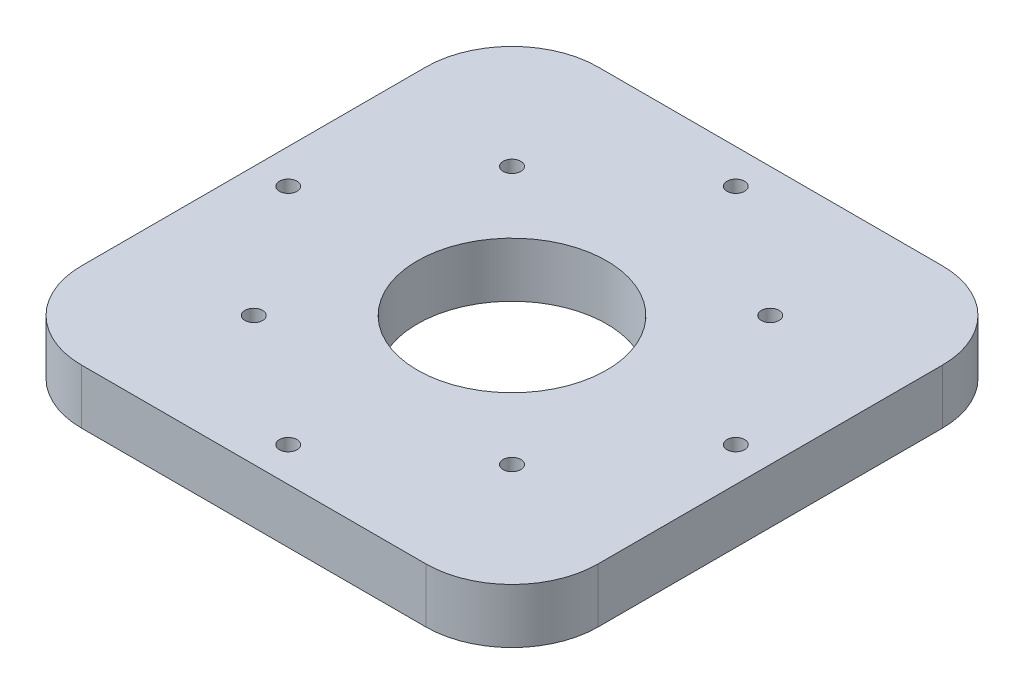
SolidWorks part; units mm, degrees
material "Oak"
ref_plane "Front Plane" through (0, 0, 0) normal (0, 0, 1) x (1, 0, 0)
ref_plane "Top Plane" through (0, 0, 0) normal (0, 1, 0) x (1, 0, 0)
ref_plane "Right Plane" through (0, 0, 0) normal (1, 0, 0) x (0, 0, -1)
sketch "Sketch3" plane through (0, 0, 0) normal (0, 1, 0) x (1, 0, 0)
  line L1 (40, -46.6704) -> (100, -46.6704)
  line L2 (40, -46.6704) -> (40, -106.6704)
  line L3 (40, -106.6704) -> (100, -106.6704)
  line L4 (100, -46.6704) -> (100, -106.6704)
  line L5 (70, -76.6704) -> (85, -76.6704) construction
  line L6 (70, -76.6704) -> (70, -91.6704) construction
  line L7 (70, -91.6704) -> (85, -91.6704) construction
  line L8 (85, -76.6704) -> (85, -91.6704) construction
  line L9 (55, -61.6704) -> (85, -61.6704) construction
  line L10 (55, -61.6704) -> (55, -91.6704) construction
  line L11 (55, -91.6704) -> (85, -91.6704) construction
  line L12 (85, -61.6704) -> (85, -91.6704) construction
  line L13 (55, -61.6704) -> (85, -91.6704) construction
  line L14 (55, -91.6704) -> (85, -61.6704) construction
  circle A0 centre (70, -76.6704) radius 11
  circle A1 centre (55, -61.6704) radius 1.025
  circle A2 centre (85, -61.6704) radius 1.025
  circle A3 centre (85, -91.6704) radius 1.025
  circle A4 centre (55, -91.6704) radius 1.025
  dimension "D5" = 22
  dimension "D8" = 2.05
  dimension "D9" = 2.05
  dimension "D10" = 2.05
  dimension "D11" = 2.05
  dimension "D1" = 60
  dimension "D2" = 60
  dimension "D3" = 30
  dimension "D4" = 30
  dimension "D6" = 15
  dimension "D7" = 15
extrude "Boss-Extrude1" add sketch "Sketch3" along normal blind 6.35
fillet "Fillet1" radius 10 4 edges at (100, 3.175, 106.6704) (100, 3.175, 46.6704) (40, 3.175, 46.6704) (40, 3.175, 106.6704)
sketch "Sketch4" plane through (0, 6.35, 0) normal (0, 1, 0) x (1, 0, 0)
  line L0 (40, -56.6704) -> (40, -96.6704) construction
  line L1 (100, -96.6704) -> (100, -56.6704) construction
  line L2 (90, -46.6704) -> (50, -46.6704) construction
  line L3 (50, -106.6704) -> (90, -106.6704) construction
  line L4 (70, -50.6704) -> (70, -102.6704) construction
  line L5 (44, -76.6704) -> (96, -76.6704) construction
  circle A0 centre (44, -76.6704) radius 1.025
  circle A1 centre (96, -76.6704) radius 1.025
  circle A2 centre (70, -50.6704) radius 1.025
  circle A3 centre (70, -102.6704) radius 1.025
  dimension "D1" = 2.05
  dimension "D2" = 2.05
  dimension "D9" = 2.05
  dimension "D10" = 2.05
  dimension "D3" = 4
  dimension "D4" = 4
  dimension "D5" = 4
  dimension "D6" = 4
  dimension "D7" = 30
  dimension "D8" = 30
extrude "Cut-Extrude1" cut sketch "Sketch4" against normal through all
